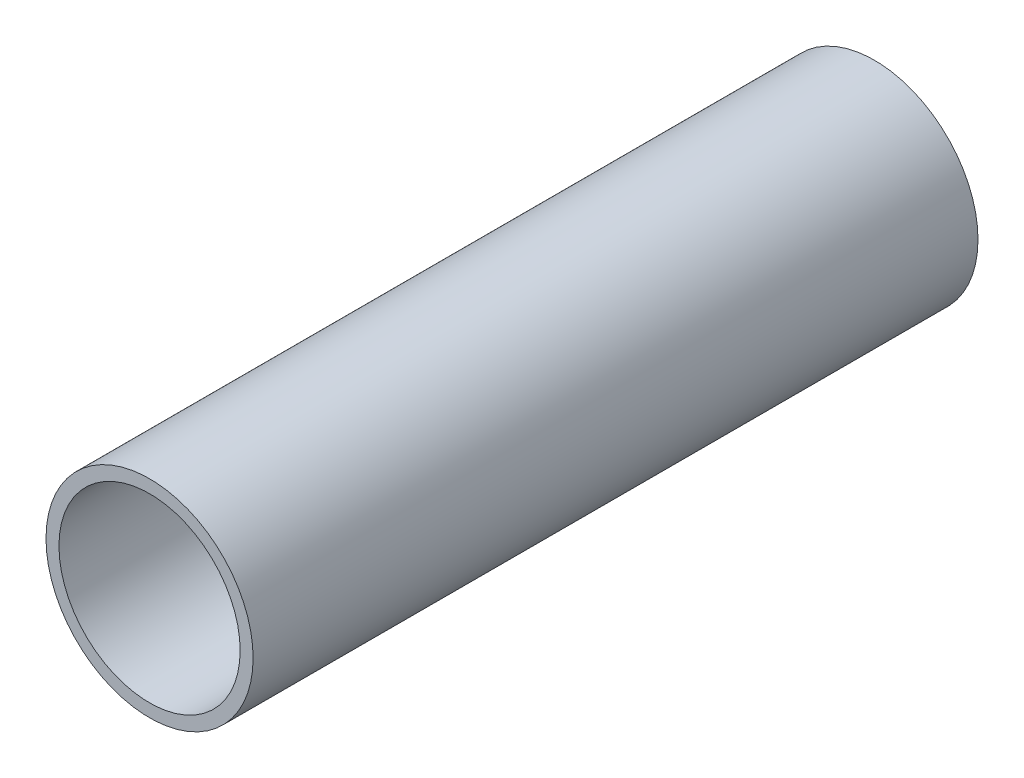
SolidWorks part; units mm, degrees
ref_plane "Front Plane" through (0, 0, 0) normal (0, 0, 1) x (1, 0, 0)
ref_plane "Top Plane" through (0, 0, 0) normal (0, 1, 0) x (1, 0, 0)
ref_plane "Right Plane" through (0, 0, 0) normal (1, 0, 0) x (0, 0, -1)
sketch "Sketch1" plane through (0, 0, 0) normal (0, 0, 1) x (1, 0, 0)
  line L0 (-50.8, 0) -> (50.8, 0) construction
  line L1 (0, -50.8) -> (0, 50.8) construction
  circle A0 centre (0, 0) radius 50.8
  circle A1 centre (0, 0) radius 44.45
  point P4 (0, 0)
  point P9 (0, 0)
  point P10 (44.45, 0)
  dimension "D1" = 88.9
  dimension "OD" = 101.6
  dimension "Wall Thickness" = 6.35
sketch "Sketch2" plane through (0, 0, 0) normal (1, 0, 0) x (0, 0, -1)
  line L0 (304.8, 50.8) -> (-304.8, 50.8) construction
  line L1 (0, 50.8) -> (0, -50.8) construction
  point P3 (-187.96, 50.8)
  point P4 (0, 50.8)
  point P5 (187.96, 50.8)
  dimension "D1" = 116.84
  dimension "D2" = 116.84
  dimension "Length" = 609.6
sketch "Sketch3" plane through (0, 0, 0) normal (0, 0, 1) x (1, 0, 0)
  line L0 (0, -50.8) -> (0, 50.8) construction
  circle A0 centre (0, 0) radius 50.8
  circle A1 centre (0, 0) radius 44.45
  circle A2 centre (0, 0) radius 44.45 construction
extrude "Boss-Extrude1" add sketch "Sketch3" along normal mid plane 355.6
equation "\"D1@Boss-Extrude1\" = \"Length@Sketch2\""
equation "\"D1@Sketch2\"=\"OD@Sketch1\"*1.15"
equation "\"D2@Sketch2\"=\"D1@Sketch2\""
